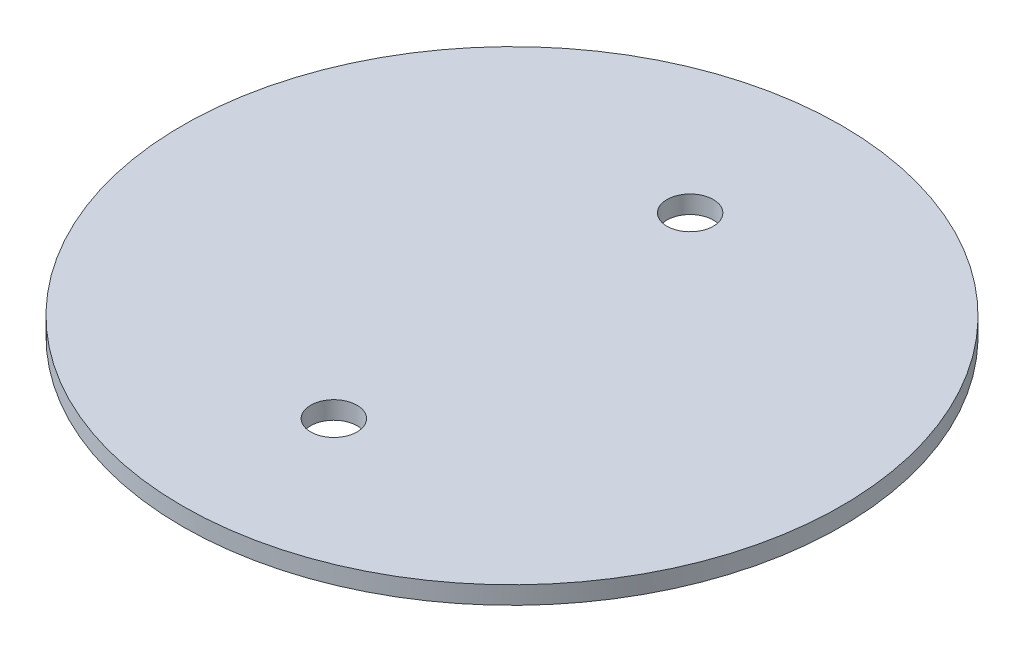
SolidWorks part; units mm, degrees
ref_plane "Front Plane" through (0, 0, 0) normal (0, 0, 1) x (1, 0, 0)
ref_plane "Top Plane" through (0, 0, 0) normal (0, 1, 0) x (1, 0, 0)
ref_plane "Right Plane" through (0, 0, 0) normal (1, 0, 0) x (0, 0, -1)
sketch "Sketch1" plane through (0, 0, 0) normal (0, 1, 0) x (1, 0, 0)
  circle A36 centre (0, 0) radius 37
  point P38 (0, 0)
  dimension "D6" = 74
extrude "Boss-Extrude1" add sketch "Sketch1" along normal blind 2
sketch "Sketch2" plane through (0, 2, 0) normal (0, 1, 0) x (1, 0, 0)
  line L0 (0, 20) -> (0, 0) construction
  line L1 (0, 0) -> (15.2532, 0) construction
  circle A0 centre (0, 20) radius 2.6
  circle A1 centre (0, -20) radius 2.6
  dimension "D1" = 5.2
  dimension "D2" = 20
extrude "Cut-Extrude1" cut sketch "Sketch2" against normal blind 3
